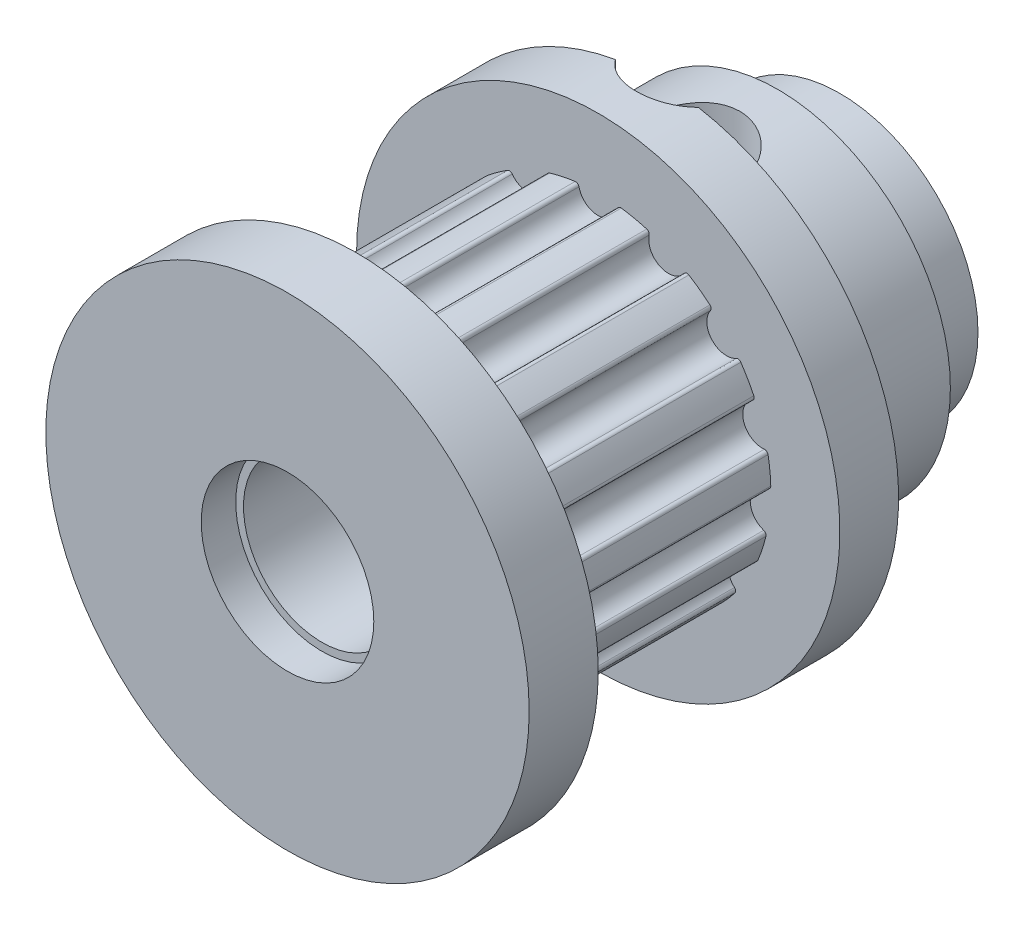
SolidWorks part; units mm, degrees
ref_plane "Plano frontal" through (0, 0, 0) normal (0, 0, 1) x (1, 0, 0)
ref_plane "Plano superior" through (0, 0, 0) normal (0, 1, 0) x (1, 0, 0)
ref_plane "Plano direito" through (0, 0, 0) normal (1, 0, 0) x (0, 0, -1)
sketch "Esboço1" plane through (0, 0, 0) normal (0, 0, 1) x (1, 0, 0)
  circle A0 centre (0, 0) radius 5
  circle A1 centre (0, 0) radius 2.275
  dimension "D1" = 4.55
  dimension "D2" = 10
extrude "Ressalto-extrusão1" add sketch "Esboço1" along normal blind 13.2
sketch "Esboço2" plane through (0, 0, 13.2) normal (0, 0, 1) x (1, 0, 0)
  circle A0 centre (0, 0) radius 2.275
  circle A1 centre (0, 0) radius 4
  circle A2 centre (0, 0) radius 2.275 construction
  dimension "D1" = 8
extrude "Ressalto-extrusão2" add sketch "Esboço2" against normal blind 15
ref_plane "Plano2" through (0, 0, 5) normal (0, 0, -1) x (-1, 0, 0)
sketch "Esboço7" plane through (0, 0, 13.2) normal (0, 0, 1) x (1, 0, 0)
  line L0 (0, 0) -> (0, 5) construction
  line L1 (0, 0) -> (2.0337, 4.5677) construction
  circle A0 centre (0, 5) radius 0.57
  circle A1 centre (0, 0) radius 5 construction
  circle A2 centre (2.0337, 4.5677) radius 0.57
  circle A3 centre (3.7157, 3.3457) radius 0.57
  circle A4 centre (4.7553, 1.5451) radius 0.57
  circle A5 centre (4.9726, -0.5226) radius 0.57
  circle A6 centre (4.3301, -2.5) radius 0.57
  circle A7 centre (2.9389, -4.0451) radius 0.57
  circle A8 centre (1.0396, -4.8907) radius 0.57
  circle A9 centre (-1.0396, -4.8907) radius 0.57
  circle A10 centre (-2.9389, -4.0451) radius 0.57
  circle A11 centre (-4.3301, -2.5) radius 0.57
  circle A12 centre (-4.9726, -0.5226) radius 0.57
  circle A13 centre (-4.7553, 1.5451) radius 0.57
  circle A14 centre (-3.7157, 3.3457) radius 0.57
  circle A15 centre (-2.0337, 4.5677) radius 0.57
  dimension "D3" = 1.14
  dimension "D2" = 24
  dimension "D1" = 15
extrude "Corte-extrusão2" cut sketch "Esboço7" against normal blind 8
fillet "Filete1" radius 0.1 30 edges at (-2.5403, 4.3066, 9.2) (-1.5006, 4.7695, 9.2) (-0.5691, 4.9675, 9.2) (0.5691, 4.9675, 9.2) (-2.4594, -4.3533, 9.2) (-3.3802, -3.6843, 9.2) (-4.0175, -2.9766, 9.2) (-4.5865, -1.9909, 9.2) (-4.8808, -1.0852, 9.2) (-4.9998, 0.0467, 9.2) (1.5894, -4.7406, 9.2) (0.4762, -4.9773, 9.2) (-0.4762, -4.9773, 9.2) (-1.5894, -4.7406, 9.2) (3.3802, -3.6843, 9.2) (2.4594, -4.3533, 9.2) (-4.9002, 0.9938, 9.2) (-4.5485, 2.0763, 9.2) (4.5865, -1.9909, 9.2) (4.0175, -2.9766, 9.2) (4.9998, 0.0467, 9.2) (4.8808, -1.0852, 9.2) (4.5485, 2.0763, 9.2) (4.9002, 0.9938, 9.2) (3.3108, 3.7468, 9.2) (4.0724, 2.901, 9.2) (2.5403, 4.3066, 9.2) (1.5006, 4.7695, 9.2) (-4.0724, 2.901, 9.2) (-3.3108, 3.7468, 9.2)
sketch "Esboço3" plane through (0, 0, 5) normal (0, 0, -1) x (-1, 0, 0)
  circle A1 centre (0, 0) radius 7
  circle A2 centre (0, 0) radius 2.275
  circle A3 centre (0, 0) radius 2.275 construction
  dimension "D1" = 14
extrude "Ressalto-extrusão3" add sketch "Esboço3" along normal blind 1.5 and the other way blind 0.2
sketch "Esboço4" plane through (0, 0, 13.2) normal (0, 0, 1) x (1, 0, 0)
  circle A0 centre (0, 0) radius 2.275
  circle A1 centre (0, 0) radius 7
  circle A2 centre (0, 0) radius 7 construction
  circle A3 centre (0, 0) radius 2.275 construction
extrude "Ressalto-extrusão4" add sketch "Esboço4" against normal blind 1
ref_plane "Plano1" through (0, 0, -3) normal (0, 0, -1) x (-1, 0, 0)
sketch "Esboço6" plane through (0, 0, 0) normal (0, 1, 0) x (1, 0, 0)
  line L0 (0, 0) -> (0, -5.2) construction
  line L1 (-7, -5.2) -> (7, -5.2) construction
  circle A0 centre (0, -2.6) radius 1.5
  dimension "D1" = 3
extrude "Corte-extrusão1" cut sketch "Esboço6" along normal through all
fillet "Filete2" radius 0.5 1 edges at (2.275, 0, -1.8)
sketch "Esboço8" plane through (0, 0, 13.2) normal (0, 0, 1) x (1, 0, 0)
  circle A0 centre (0, 0) radius 2.5
  circle A1 centre (0, 0) radius 7
  circle A2 centre (0, 0) radius 7 construction
extrude "Ressalto-extrusão5" add sketch "Esboço8" along normal blind 1
